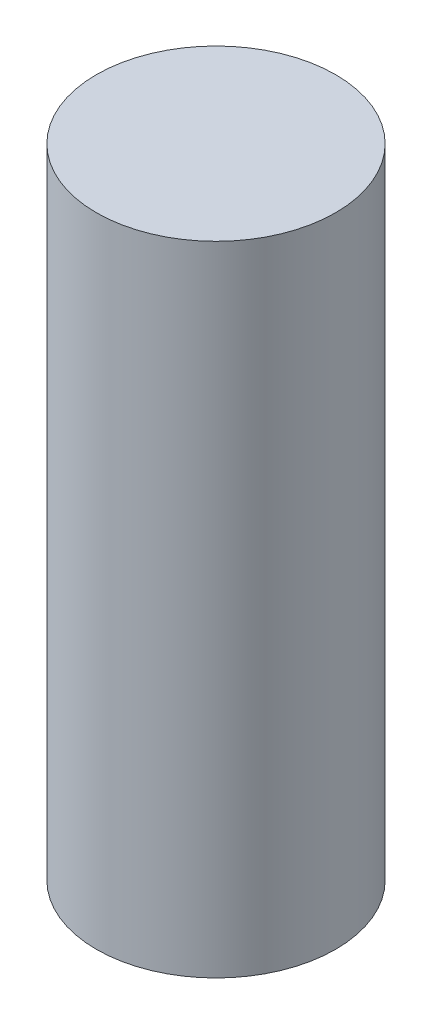
SolidWorks part; units mm, degrees
ref_plane "Front Plane" through (0, 0, 0) normal (0, 0, 1) x (1, 0, 0)
ref_plane "Top Plane" through (0, 0, 0) normal (0, 1, 0) x (1, 0, 0)
ref_plane "Right Plane" through (0, 0, 0) normal (1, 0, 0) x (0, 0, -1)
sketch "Sketch1" plane through (0, 0, 0) normal (0, 1, 0) x (1, 0, 0)
  circle A0 centre (0, 0) radius 3
  dimension "D1" = 6
extrude "Boss-Extrude1" add sketch "Sketch1" along normal blind 16
